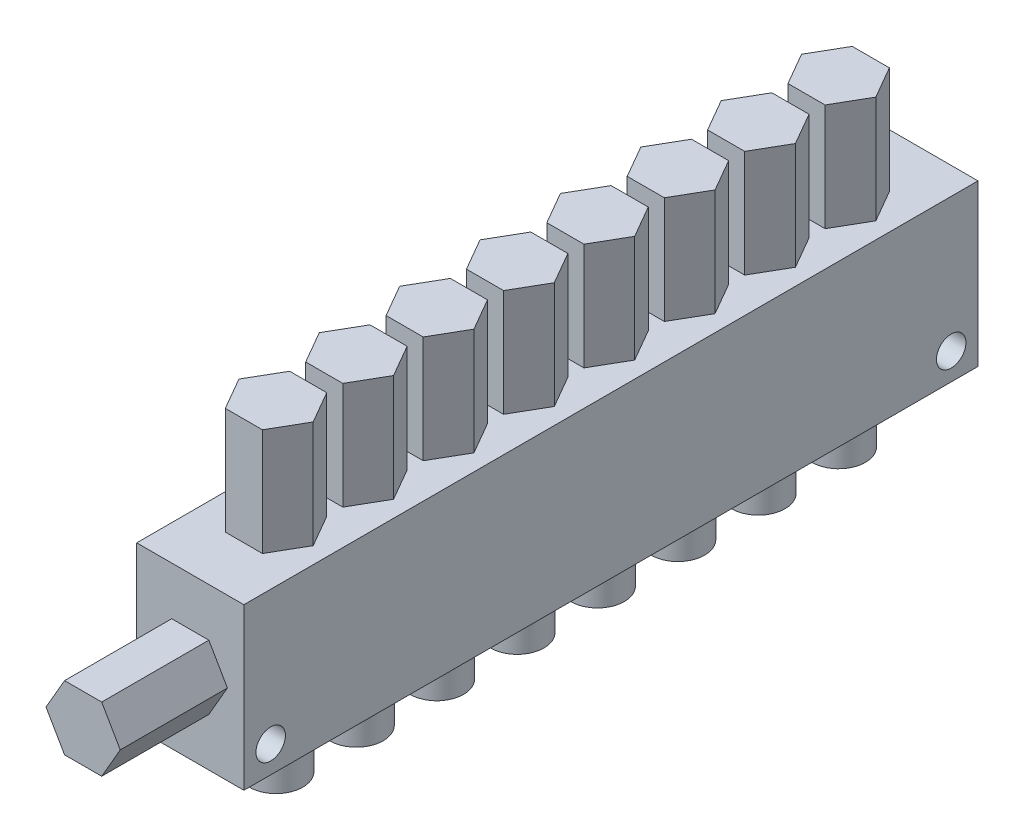
SolidWorks part; units mm, degrees
material "H62"
ref_plane "前视" through (0, 0, 0) normal (0, 0, 1) x (1, 0, 0)
ref_plane "上视" through (0, 0, 0) normal (0, 1, 0) x (1, 0, 0)
ref_plane "右视" through (0, 0, 0) normal (1, 0, 0) x (0, 0, -1)
sketch "草图1" plane through (0, 0, 0) normal (1, 0, 0) x (0, 0, -1)
  line L1 (-68.5, -15) -> (68.5, -15)
  line L2 (-68.5, -15) -> (-68.5, 15)
  line L3 (-68.5, 15) -> (68.5, 15)
  line L4 (68.5, -15) -> (68.5, 15)
  line L5 (-68.5, -15) -> (68.5, 15) construction
  line L6 (-68.5, 15) -> (68.5, -15) construction
  point P0 (0, 0)
  dimension "D1" = 137
  dimension "D2" = 30
extrude "凸台-拉伸1" add sketch "草图1" along normal mid plane 20
hole_wizard "M5 间隙孔1" positions "草图3" profile "草图2" hole size "M5" standard "Gb" end condition through all
sketch "草图3" plane through (10, 0, 0) normal (1, 0, 0) x (0, 0, -1)
  line L0 (0, 15) -> (0, -15) construction
  line L1 (68.5, 15) -> (-68.5, 15) construction
  line L2 (-68.5, -15) -> (68.5, -15) construction
  point P0 (-63.5, -10)
  point P10 (63.5, -10)
  dimension "D1" = 127
  dimension "D2" = 5
sketch "草图2" plane through (10, -10, 63.5) normal (0, 1, 0) x (0, 0, -1)
  line L0 (0, 0) -> (0, 20)
  line L1 (0, 20) -> (2.75, 20)
  line L2 (2.75, 20) -> (2.75, 0)
  line L5 (2.75, 0) -> (0, 0)
  line L11 (0, -6.35) -> (0, 107.95) construction
  dimension "通孔孔直径" = 5.5
  dimension "通孔孔深度" = 20
sketch "草图4" plane through (0, 15, 0) normal (0, 1, 0) x (1, 0, 0)
  line L0 (10, 0) -> (-19.9353, 0) construction
  line L1 (6.9282, -52.5) -> (3.4641, -46.5)
  line L2 (3.4641, -46.5) -> (-3.4641, -46.5)
  line L3 (-3.4641, -46.5) -> (-6.9282, -52.5)
  line L4 (-6.9282, -52.5) -> (-3.4641, -58.5)
  line L5 (-3.4641, -58.5) -> (3.4641, -58.5)
  line L6 (3.4641, -58.5) -> (6.9282, -52.5)
  line L7 (10, 68.5) -> (10, -68.5) construction
  line L8 (0, -68.5) -> (0, -52.5) construction
  line L9 (10, -68.5) -> (-10, -68.5) construction
  circle A0 centre (0, -52.5) radius 6 construction
  dimension "D1" = 12
  dimension "D2" = 105
extrude "凸台-拉伸2" add sketch "草图4" along normal blind 20
sketch "草图6" plane through (0, 0, 0) normal (1, 0, 0) x (0, 0, -1)
  line L0 (-52.5, 35) -> (-52.5, -25) construction
  line L1 (-52.5, -15) -> (-49.5, -15)
  line L2 (-68.5, -15) -> (68.5, -15) construction
  line L3 (-49.5, -15) -> (-49.5, -20)
  line L4 (-49.5, -20) -> (-47.5, -20)
  line L5 (-47.5, -20) -> (-47.5, -25)
  line L6 (-47.5, -25) -> (-52.5, -25)
  line L7 (-52.5, -25) -> (-52.5, -15)
  dimension "D1" = 6
  dimension "D2" = 5
  dimension "D3" = 10
  dimension "D4" = 10
revolve "旋转1" add sketch "草图6" angle 360 about L0
pattern_linear "阵列(线性)1" count 8 spacing 15 along (0, 0, -1) of "凸台-拉伸2", "旋转1"
sketch "草图5" plane through (0, 0, 68.5) normal (0, 0, 1) x (1, 0, 0)
  line L1 (3.4641, 6) -> (-3.4641, 6)
  line L2 (-3.4641, 6) -> (-6.9282, 0)
  line L3 (-6.9282, 0) -> (-3.4641, -6)
  line L4 (-3.4641, -6) -> (3.4641, -6)
  line L5 (3.4641, -6) -> (6.9282, 0)
  line L6 (6.9282, 0) -> (3.4641, 6)
  line L7 (-3.4641, 15) -> (3.4641, 15) construction
  circle A0 centre (0, 0) radius 6 construction
extrude "凸台-拉伸4" add sketch "草图5" along normal blind 20
equation "\"15X8\"=85.8375"
